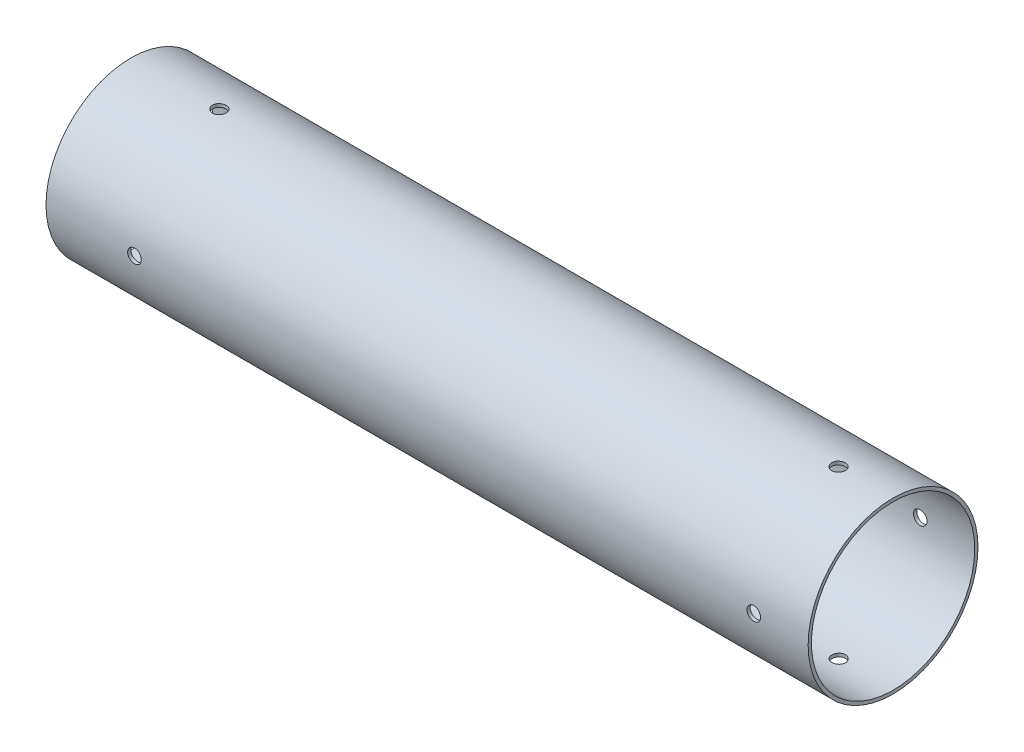
SolidWorks part; units mm, degrees
ref_plane "Front Plane" through (0, 0, 0) normal (1, 0, 0) x (0, 1, 0)
ref_plane "Top Plane" through (0, 0, 0) normal (0, 0, 1) x (0, 1, 0)
ref_plane "Right Plane" through (0, 0, 0) normal (0, 1, 0) x (-1, 0, 0)
sketch "Sketch1" plane through (0, 0, 0) normal (1, 0, 0) x (0, 1, 0)
  circle A0 centre (0, 0) radius 39.624
  circle A1 centre (0, 0) radius 38.1
  dimension "D1" = 79.248
  dimension "D2" = 76.2
extrude "Boss-Extrude1" add sketch "Sketch1" along normal blind 355.6
sketch "Sketch2" plane through (0, 0, 0) normal (0, 1, 0) x (-1, 0, 0)
  line L0 (-355.6, 39.624) -> (-355.6, -39.624) construction
  line L1 (-330.2, 0) -> (-355.6, 0) construction
  circle A0 centre (-330.2, 0) radius 3.175
  dimension "D1" = 6.35
  dimension "D2" = 25.4
extrude "Cut-Extrude1" cut sketch "Sketch2" along normal through all
pattern_circular "CirPattern1" count 4 over 360 about axis through (355.6, 0, 0) along (-1, 0, 0) of "Cut-Extrude1"
sketch "Sketch3" plane through (0, 0, 0) normal (0, 1, 0) x (-1, 0, 0)
  circle A0 centre (-41.275, 0) radius 3.175
  dimension "D1" = 6.35
  dimension "D2" = 41.275
extrude "Cut-Extrude2" cut sketch "Sketch3" along normal through all
pattern_circular "CirPattern2" count 4 over 360 about axis through (355.6, 0, 0) along (-1, 0, 0) of "Cut-Extrude2"
